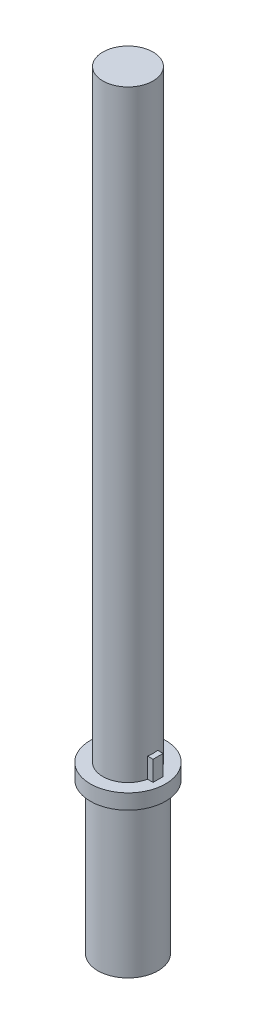
SolidWorks part; units mm, degrees
ref_plane "前视基准面" through (0, 0, 0) normal (0, 0, 1) x (1, 0, 0)
ref_plane "上视基准面" through (0, 0, 0) normal (0, 1, 0) x (1, 0, 0)
ref_plane "右视基准面" through (0, 0, 0) normal (1, 0, 0) x (0, 0, -1)
sketch "草图1" plane through (0, 0, 0) normal (0, 1, 0) x (1, 0, 0)
  circle A0 centre (0, 0) radius 5.25
  circle A1 centre (0, 0) radius 6
  dimension "D1" = 10.5
  dimension "D2" = 12
extrude "凸台-拉伸2" add sketch "草图1" along normal blind 30 contours A1 | A0
sketch "草图2" plane through (0, 30, 0) normal (0, 1, 0) x (1, 0, 0)
  circle A0 centre (0, 0) radius 7.5
  dimension "D1" = 15
extrude "凸台-拉伸3" add sketch "草图2" along normal blind 3
sketch "草图3" plane through (0, 33, 0) normal (0, 1, 0) x (1, 0, 0)
  circle A0 centre (0, 0) radius 5
  dimension "D1" = 10
extrude "凸台-拉伸4" add sketch "草图3" along normal blind 120
sketch "草图4" plane through (0, 33, 0) normal (0, 1, 0) x (1, 0, 0)
  line L0 (0, 0) -> (5, 0) construction
  line L1 (0, 0) -> (0, 5) construction
  line L2 (0, -1) -> (6, -1)
  line L3 (0, 0) -> (6, 0)
  line L4 (0, -1) -> (0, 1)
  line L5 (0, 1) -> (6, 1)
  line L6 (6, -1) -> (6, 1)
  circle M7 centre (0, 0) radius 5
  dimension "D1" = 6
  dimension "D2" = 1
extrude "凸台-拉伸6" add sketch "草图4" along normal blind 4 contours L3 L6 L5 M7 | L2 L6 L3 M7
